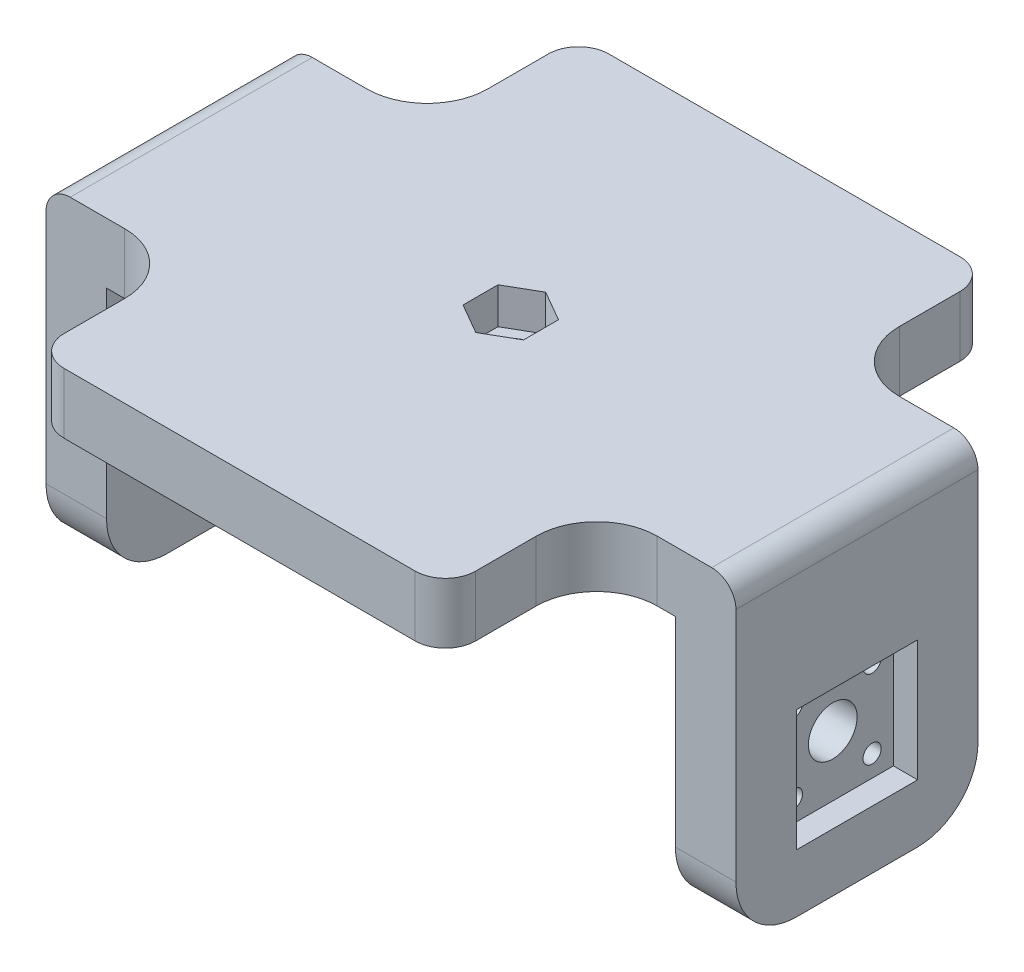
SolidWorks part; units mm, degrees
ref_plane "Front Plane" through (0, 0, 0) normal (0, 0, 1) x (1, 0, 0)
ref_plane "Top Plane" through (0, 0, 0) normal (0, 1, 0) x (1, 0, 0)
ref_plane "Right Plane" through (0, 0, 0) normal (1, 0, 0) x (0, 0, -1)
sketch "Sketch1" plane through (0, 0, 0) normal (0, 0, 1) x (1, 0, 0)
  line L0 (10, 0) -> (10, 43)
  line L1 (0, 0) -> (10, 0)
  line L2 (0, 0) -> (0, 53)
  line L3 (0, 53) -> (114, 53)
  line L4 (114, 0) -> (114, 53)
  line L5 (10, 43) -> (104, 43)
  line L6 (104, 43) -> (104, 0)
  line L7 (104, 0) -> (114, 0)
  dimension "D1" = 94
  dimension "D2" = 43
  dimension "D3" = 10
  dimension "D4" = 10
  dimension "D5" = 53
extrude "Boss-Extrude1" add sketch "Sketch1" against normal blind 40
sketch "Sketch2" plane through (10, 0, 0) normal (1, 0, 0) x (0, 0, -1)
  line L0 (5, 4.6351) -> (5, 34.6351) construction
  line L1 (5, 4.6351) -> (35, 4.6351) construction
  line L2 (5, 34.6351) -> (35, 34.6351) construction
  line L3 (35, 4.6351) -> (35, 34.6351) construction
  line L5 (5, 4.6351) -> (35, 34.6351) construction
  line L6 (5, 34.6351) -> (35, 4.6351) construction
  circle A0 centre (20, 19.6351) radius 12.5
  point P0 (20, 19.6351)
  dimension "D4" = 4.6351
  dimension "D1" = 30
  dimension "D2" = 30
  dimension "D3" = 20
extrude "Cut-Extrude1" cut sketch "Sketch2" against normal blind 4.4775
fillet "Fillet1" radius 10 4 edges at (109, 0, -40) (109, 0, 0) (5, 0, -40) (5, 0, 0)
sketch "Sketch4" plane through (7.725, 0, 0) normal (1, 0, 0) x (0, 0, -1)
  circle A0 centre (20, 19.6351) radius 2.5
  dimension "D1" = 5
extrude "Cut-Extrude2" cut sketch "Sketch4" against normal blind 14.2 and the other way blind 131.2
sketch "Sketch6" plane through (0, 53, 0) normal (0, 1, 0) x (1, 0, 0)
  line L1 (23, -25) -> (91, -25)
  line L2 (23, -25) -> (23, 65)
  line L3 (23, 65) -> (91, 65)
  line L4 (91, -25) -> (91, 65)
  line L5 (23, -25) -> (91, 65) construction
  line L6 (23, 65) -> (91, -25) construction
  line L7 (114, 40) -> (0, 40) construction
  point P0 (57, 20)
  dimension "D1" = 90
  dimension "D2" = 68
  dimension "D3" = 57
  dimension "D4" = 20
extrude "Boss-Extrude4" add sketch "Sketch6" against normal blind 10
fillet "Fillet2" radius 10 4 edges at (91, 48, -40) (91, 48, 0) (23, 48, -40) (23, 48, 0)
fillet "Fillet3" radius 5 4 edges at (91, 48, 25) (23, 48, 25) (23, 48, -65) (91, 48, -65)
fillet "Fillet4" radius 4 2 edges at (114, 53, -20) (0, 53, -20)
sketch "Sketch7" plane through (7.725, 0, 0) normal (1, 0, 0) x (0, 0, -1)
  circle A0 centre (20, 19.6351) radius 3.9
  dimension "D1" = 7.8
extrude "Cut-Extrude3" cut sketch "Sketch7" against normal blind 0.85 from surface at -2.2025 starting at face at (5.5225, 19.6351, -32.5)
sketch "Sketch8" plane through (0, 53, 0) normal (0, 1, 0) x (1, 0, 0)
  line L0 (114, 40) -> (114, 0) construction
  line L1 (28, -25) -> (86, -25) construction
  circle A0 centre (57, 20) radius 3.25
  dimension "D3" = 6.5
  dimension "D1" = 57
  dimension "D2" = 45
extrude "Cut-Extrude4" cut sketch "Sketch8" against normal blind 10
sketch "Sketch9" plane through (114, 0, 0) normal (1, 0, 0) x (0, 0, -1)
  circle A0 centre (20, 19.6351) radius 4.025
  dimension "D1" = 8.05
extrude "Cut-Extrude5" cut sketch "Sketch9" against normal blind 12
sketch "Sketch10" plane through (114, 0, 0) normal (1, 0, 0) x (0, 0, -1)
  line L1 (9.975, 9.6101) -> (30.025, 9.6101)
  line L2 (9.975, 9.6101) -> (9.975, 29.6601)
  line L3 (9.975, 29.6601) -> (30.025, 29.6601)
  line L4 (30.025, 9.6101) -> (30.025, 29.6601)
  line L5 (9.975, 9.6101) -> (30.025, 29.6601) construction
  line L6 (9.975, 29.6601) -> (30.025, 9.6101) construction
  point P0 (20, 19.6351)
  dimension "D1" = 20.05
  dimension "D2" = 20.05
extrude "Cut-Extrude6" cut sketch "Sketch10" against normal blind 4
sketch "Sketch14" plane through (0, 53, 0) normal (0, 1, 0) x (1, 0, 0)
  line L0 (56.8729, 25.695) -> (61.8729, 22.8082)
  line L1 (61.8729, 22.8082) -> (61.8729, 17.0347)
  line L2 (61.8729, 17.0347) -> (56.8729, 14.148)
  line L3 (56.8729, 14.148) -> (51.8729, 17.0347)
  line L4 (51.8729, 17.0347) -> (51.8729, 22.8082)
  line L5 (51.8729, 22.8082) -> (56.8729, 25.695)
extrude "Cut-Extrude7" cut sketch "Sketch14" against normal blind 6 contours L2 L3 L4 L5 L0 L1
sketch "Sketch15" plane through (104, 0, 0) normal (-1, 0, 0) x (0, 0, 1)
  circle A0 centre (-26.5, 26.1351) radius 1.5
  circle A1 centre (-13.5, 26.1351) radius 1.5
  circle A2 centre (-13.5, 13.1351) radius 1.5
  circle A3 centre (-26.5, 13.1351) radius 1.5
  circle A4 centre (-13.4008, 24.6117) radius 0.0267
sketch "Sketch18" plane through (104, 0, 0) normal (-1, 0, 0) x (0, 0, 1)
  line L0 (-13.429, 23.2499) -> (-11.8413, 23.2499) construction
  line L1 (-15.0489, 28.9136) -> (-11.9101, 28.9136)
  line L3 (-15.151, 23.2499) -> (-11.8916, 23.2499)
  line L5 (-15.0489, 28.9136) -> (-11.8916, 23.2499) construction
  line L6 (-15.151, 23.2499) -> (-11.9101, 28.9136) construction
  line L7 (-13.4702, 26.0817) -> (-10.2705, 26.0817) construction
  line L8 (-10.2705, 26.0817) -> (-13.4702, 26.0817) construction
  line L9 (-13.4702, 26.0817) -> (-16.734, 26.0817) construction
  line L10 (-16.734, 26.0817) -> (-15.0489, 28.9136)
  line L11 (-11.9101, 28.9136) -> (-10.2705, 26.0817)
  line L12 (-10.2705, 26.0817) -> (-11.8916, 23.2499)
  line L13 (-15.151, 23.2499) -> (-16.734, 26.0817)
  line L14 (-13.5, 13.1351) -> (-26.5, 13.1351) construction
  line L15 (-26.5, 13.1351) -> (-20, 13.1351) construction
  line L16 (-20, 13.1351) -> (-20, 32.3861) construction
  line L17 (-20, 32.3861) -> (-20, 19.6351) construction
  line L18 (-20, 19.6351) -> (-8.7366, 19.6351) construction
  line L19 (-8.7366, 19.6351) -> (-30.7611, 19.6351) construction
  line L20 (-23.266, 26.0817) -> (-24.9511, 28.9136)
  line L21 (-24.849, 23.2499) -> (-23.266, 26.0817)
  line L22 (-24.849, 23.2499) -> (-28.1084, 23.2499)
  line L23 (-29.7295, 26.0817) -> (-28.1084, 23.2499)
  line L24 (-28.0899, 28.9136) -> (-29.7295, 26.0817)
  line L25 (-24.9511, 28.9136) -> (-28.0899, 28.9136)
  line L26 (-16.734, 13.1886) -> (-15.0489, 10.3567)
  line L27 (-15.151, 16.0204) -> (-16.734, 13.1886)
  line L28 (-15.151, 16.0204) -> (-11.8916, 16.0204)
  line L29 (-10.2705, 13.1886) -> (-11.8916, 16.0204)
  line L30 (-11.9101, 10.3567) -> (-10.2705, 13.1886)
  line L31 (-15.0489, 10.3567) -> (-11.9101, 10.3567)
  line L32 (-24.849, 16.0204) -> (-23.266, 13.1886)
  line L33 (-24.849, 16.0204) -> (-28.1084, 16.0204)
  line L34 (-29.7295, 13.1886) -> (-28.1084, 16.0204)
  line L35 (-28.0899, 10.3567) -> (-29.7295, 13.1886)
  line L36 (-24.9511, 10.3567) -> (-28.0899, 10.3567)
  line L37 (-23.266, 13.1886) -> (-24.9511, 10.3567)
  point P0 (-13.5, 26.1351)
extrude "Cut-Extrude9" cut sketch "Sketch18" against normal blind 2.5
extrude "Cut-Extrude10" cut sketch "Sketch15" against normal up to next from offset 2.5 contours A0 | A3 | A2 | A1
